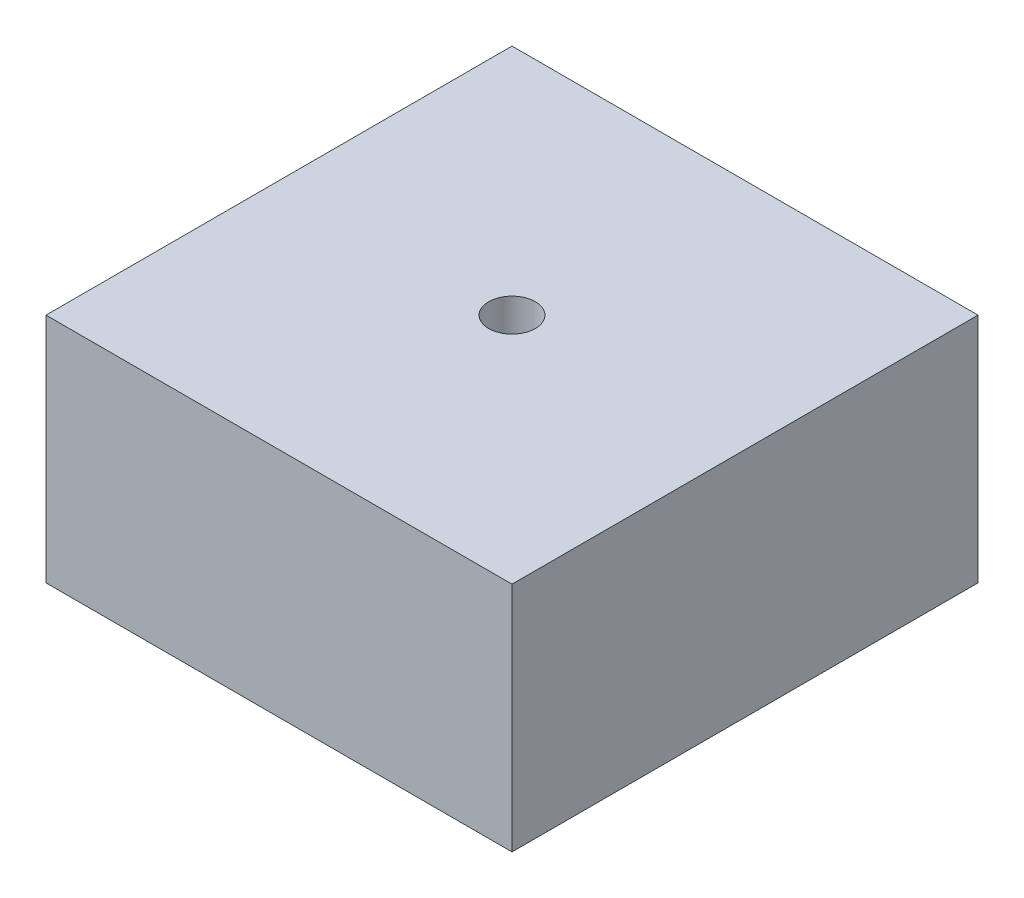
SolidWorks part; units mm, degrees
ref_plane "Front Plane" through (0, 0, 0) normal (0, 0, 1) x (1, 0, 0)
ref_plane "Top Plane" through (0, 0, 0) normal (0, 1, 0) x (1, 0, 0)
ref_plane "Right Plane" through (0, 0, 0) normal (1, 0, 0) x (0, 0, -1)
ref_plane "Plane1" through (0, -12.5, 0) normal (0, 1, 0) x (-1, 0, 0)
sketch "Sketch1" plane through (0, -12.5, 0) normal (0, 1, 0) x (1, 0, 0)
  line L1 (-50, -50) -> (50, -50)
  line L2 (-50, -50) -> (-50, 50)
  line L3 (-50, 50) -> (50, 50)
  line L4 (50, -50) -> (50, 50)
  line L5 (-50, -50) -> (50, 50) construction
  line L6 (-50, 50) -> (50, -50) construction
  point P0 (0, 0)
  dimension "D1" = 100
extrude "Boss-Extrude1" add sketch "Sketch1" along normal blind 49.7625
sketch "Sketch2" plane through (0, 37.2625, 0) normal (0, 1, 0) x (-1, 0, 0)
  circle A0 centre (0, 0) radius 5
  dimension "D1" = 10
extrude "Cut-Extrude1" cut sketch "Sketch2" against normal through all
